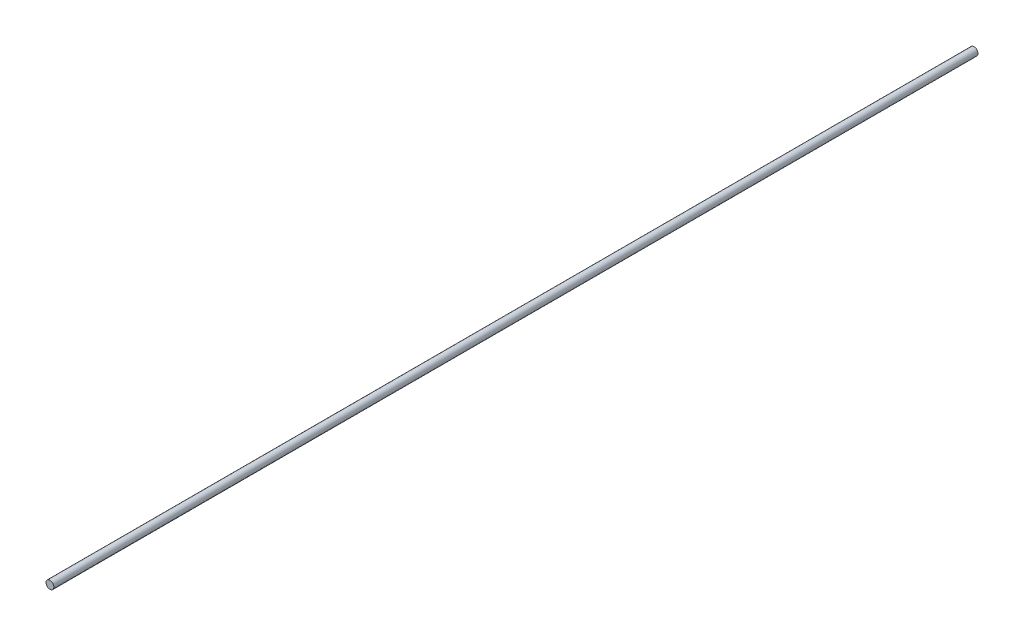
SolidWorks part; units mm, degrees
material "6061-T6 (SS)"
ref_plane "Front Plane" through (0, 0, 0) normal (0, 0, 1) x (1, 0, 0)
ref_plane "Top Plane" through (0, 0, 0) normal (0, 1, 0) x (1, 0, 0)
ref_plane "Right Plane" through (0, 0, 0) normal (1, 0, 0) x (0, 0, -1)
sketch "Sketch1" plane through (0, 0, 0) normal (0, 0, 1) x (1, 0, 0)
  circle A0 centre (0, 0) radius 6.35
  dimension "D1" = 12.7
extrude "Boss-Extrude1" add sketch "Sketch1" along normal blind 1491.234 contours A0
equation "\"Force\"= 301"
equation "\"Elastic Modulus\"= 10000000"
equation "\"MaxDeflection\"= 0.009"
equation "\"Diameter\"= 0.500"
